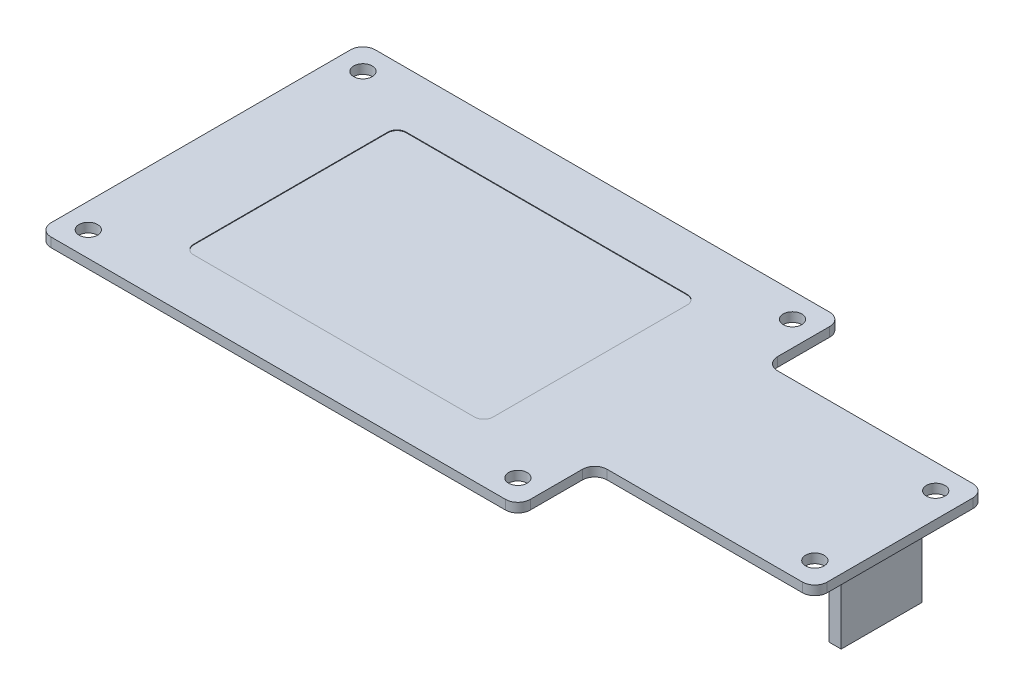
SolidWorks part; units mm, degrees
ref_plane "Front Plane" through (0, 0, 0) normal (0, 0, 1) x (1, 0, 0)
ref_plane "Top Plane" through (0, 0, 0) normal (0, 1, 0) x (1, 0, 0)
ref_plane "Right Plane" through (0, 0, 0) normal (1, 0, 0) x (0, 0, -1)
sketch "Sketch1" plane through (0, 0, 0) normal (0, 1, 0) x (1, 0, 0)
  line L0 (0, 0) -> (73.4184, 0) construction
  line L1 (-38.65, 26.15) -> (38.65, 26.15)
  line L2 (38.65, 26.15) -> (38.65, 13.75)
  line L3 (38.65, 13.75) -> (74.15, 13.75)
  line L4 (74.15, 13.75) -> (74.15, -13.75)
  line L5 (74.15, -13.75) -> (38.65, -13.75)
  line L6 (38.65, -13.75) -> (38.65, -26.15)
  line L7 (-38.65, -26.15) -> (38.65, -26.15) construction
  line L8 (-38.65, -26.15) -> (-38.65, 26.15) construction
  line L9 (-38.65, 26.15) -> (38.65, 26.15) construction
  line L10 (38.65, -26.15) -> (38.65, 26.15) construction
  line L11 (-38.65, -26.15) -> (38.65, 26.15) construction
  line L12 (-38.65, 26.15) -> (38.65, -26.15) construction
  line L13 (38.65, -26.15) -> (-38.65, -26.15)
  line L14 (38.65, 13.75) -> (74.15, 13.75) construction
  line L15 (38.65, 13.75) -> (38.65, -13.75) construction
  line L16 (38.65, -13.75) -> (74.15, -13.75) construction
  line L17 (74.15, 13.75) -> (74.15, -13.75) construction
  line L18 (-38.65, -26.15) -> (-38.65, 26.15)
  point P0 (0, 0)
  point P2 (74.15, 0)
  point P6 (0, 0)
  dimension "D1" = 52.3
  dimension "D2" = 77.3
  dimension "D3" = 27.5
  dimension "D4" = 35.5
extrude "Boss-Extrude1" add sketch "Sketch1" along normal mid plane 1.5
fillet "Fillet1" radius 2 8 edges at (-38.65, 0, -26.15) (38.65, 0, -13.75) (-38.65, 0, 26.15) (38.65, 0, -26.15) (74.15, 0, -13.75) (74.15, 0, 13.75) (38.65, 0, 13.75) (38.65, 0, 26.15)
sketch "Sketch2" plane through (0, 0.75, 0) normal (0, 1, 0) x (1, 0, 0)
  line L0 (74.15, 0) -> (-38.65, 0) construction
  line L2 (38.65, 15.75) -> (38.65, 24.15) construction
  line L3 (74.15, -11.75) -> (74.15, 11.75) construction
  line L4 (58.6809, 13.75) -> (70.1685, 13.75) construction
  line L6 (72.15, 13.75) -> (40.65, 13.75) construction
  line L7 (-1.7883, 26.15) -> (13.4283, 26.15) construction
  line L9 (0, 0) -> (0, -13.4223) construction
  line L10 (36.65, 26.15) -> (-36.65, 26.15) construction
  line L11 (38.65, 22.8666) -> (38.65, 17.44) construction
  line L13 (74.15, 3.322) -> (74.15, -2.4963) construction
  circle A0 centre (-34.65, 22.15) radius 1.5
  circle A1 centre (34.65, 22.15) radius 1.5
  circle A2 centre (34.65, -22.15) radius 1.5
  circle A3 centre (-34.65, -22.15) radius 1.5
  circle A4 centre (70.15, 9.75) radius 1.5
  circle A5 centre (70.15, -9.75) radius 1.5
  point P13 (0, 0)
  dimension "D1" = 3
  dimension "D2" = 4
  dimension "D3" = 4
  dimension "D4" = 4
  dimension "D5" = 4
extrude "Cut-Extrude1" cut sketch "Sketch2" against normal up to surface (1.5 mm away) up to face at (28.2, -0.75, 0)
sketch "Sketch4" plane through (0, 0.75, 0) normal (0, 1, 0) x (1, 0, 0)
  line L0 (-38.65, 24.15) -> (-38.65, -24.15) construction
  line L1 (-22.65, 17.15) -> (22.65, 17.15)
  line L2 (-24.15, 15.65) -> (-24.15, -15.65)
  line L3 (-22.65, -17.15) -> (22.65, -17.15)
  line L4 (24.15, 15.65) -> (24.15, -15.65)
  line L5 (-24.15, 17.15) -> (24.15, -17.15) construction
  line L6 (-24.15, -17.15) -> (24.15, 17.15) construction
  line L7 (36.65, 26.15) -> (-36.65, 26.15) construction
  arc A0 (-24.15, -15.65) -> (-22.65, -17.15) centre (-22.65, -15.65) ccw
  arc A1 (22.65, -17.15) -> (24.15, -15.65) centre (22.65, -15.65) ccw
  arc A2 (22.65, 17.15) -> (24.15, 15.65) centre (22.65, 15.65) cw
  arc A3 (-22.65, 17.15) -> (-24.15, 15.65) centre (-22.65, 15.65) ccw
  point P0 (0, 0)
  point P18 (-23.9341, 17.9221)
  dimension "D1" = 1.5
  dimension "D2" = 14.5
  dimension "D3" = 9
extrude "Cut-Extrude2" cut sketch "Sketch4" along normal blind 0.1 and the other way blind 0.1
sketch "Sketch5" plane through (0, -0.75, 0) normal (0, -1, 0) x (1, 0, 0)
  line L0 (74.15, 11.75) -> (74.15, -11.75) construction
  line L1 (71.15, 6.5) -> (69.15, 6.5)
  line L2 (71.15, 6.5) -> (71.15, -6.5)
  line L3 (71.15, -6.5) -> (69.15, -6.5)
  line L4 (69.15, 6.5) -> (69.15, -6.5)
  line L5 (30.3508, 0) -> (56.0623, 0) construction
  line L6 (72.15, -13.75) -> (40.65, -13.75) construction
  line L7 (40.65, 13.75) -> (72.15, 13.75) construction
  dimension "D1" = 2
  dimension "D2" = 3
  dimension "D3" = 13
extrude "Boss-Extrude2" add sketch "Sketch5" along normal blind 12
